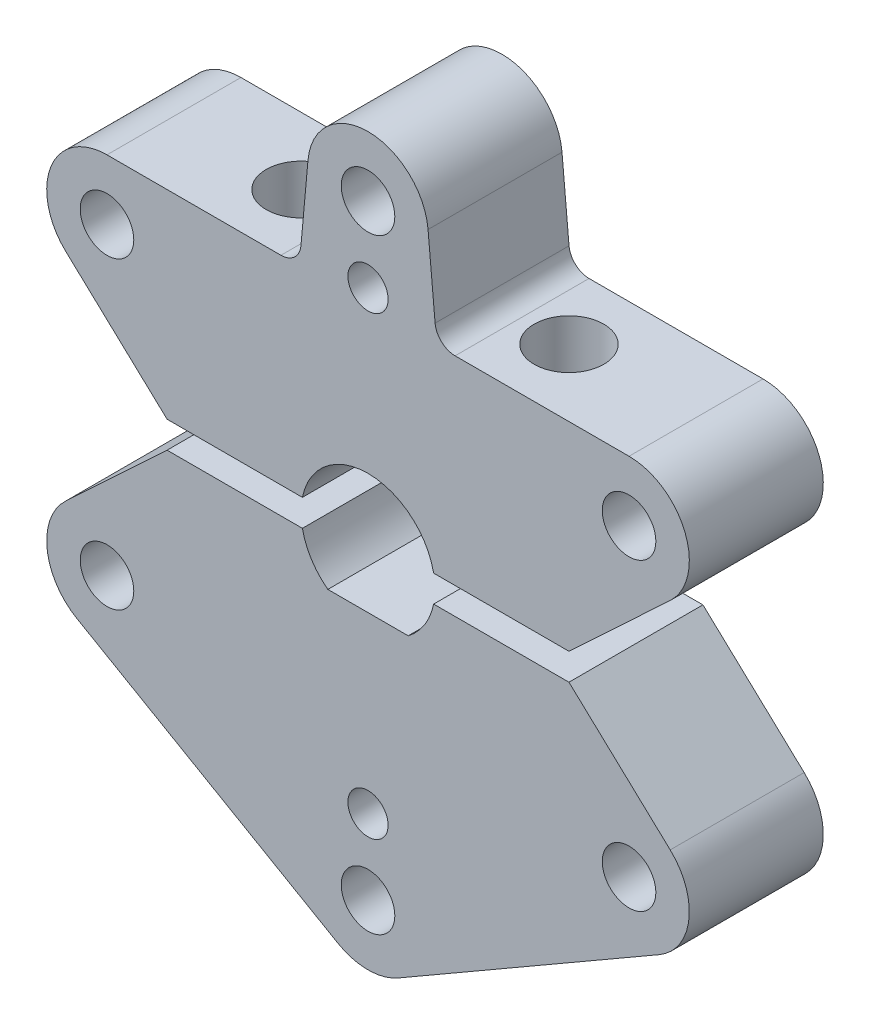
SolidWorks part; units mm, degrees
material "6061 合金"
ref_plane "前视基准面" through (0, 0, 0) normal (0, 0, 1) x (1, 0, 0)
ref_plane "上视基准面" through (0, 0, 0) normal (0, 1, 0) x (1, 0, 0)
ref_plane "右视基准面" through (0, 0, 0) normal (1, 0, 0) x (0, 0, -1)
sketch "草图1" plane through (0, 0, 0) normal (0, 0, 1) x (1, 0, 0)
  line L0 (0, 22.5) -> (0, 22.6) construction
  line L1 (0, 22.5) -> (-19.4856, 11.25) construction
  line L2 (-19.4856, 11.25) -> (-19.4856, -11.25) construction
  line L3 (-19.4856, -11.25) -> (0, -22.5) construction
  line L4 (0, -22.5) -> (19.4856, -11.25) construction
  line L5 (19.4856, -11.25) -> (19.4856, 11.25) construction
  line L6 (19.4856, 11.25) -> (0, 22.5) construction
  line L7 (-19.4856, 11.25) -> (-19.4856, 11.35) construction
  line L8 (19.4856, 11.25) -> (19.4856, 11.35) construction
  line L9 (-19.4856, -11.25) -> (-19.4856, -11.35) construction
  line L10 (0, -22.5) -> (0, -22.6) construction
  line L11 (19.4856, -11.25) -> (19.4856, -11.35) construction
  line L12 (-3, -4) -> (3, -4)
  line L13 (-15, 1) -> (-22.5579, 8.062)
  line L14 (-19.4856, 15.85) -> (-6.5, 15.85)
  line L15 (-5.0061, 17.2147) -> (-4.4817, 23.0059)
  line L16 (4.4817, 23.0059) -> (5.0061, 17.2147)
  line L17 (6.5, 15.85) -> (19.4856, 15.85)
  line L18 (22.5579, 8.062) -> (15, 1)
  line L19 (15, 1) -> (4.899, 1)
  line L20 (-5.1297, 15.85) -> (5.1297, 15.85) construction
  line L21 (-15, -1) -> (-22.5579, -8.062)
  line L22 (-4.899, 1) -> (-15, 1)
  line L23 (-21.7356, -15.2471) -> (-2.25, -26.4971)
  line L24 (2.25, -26.4971) -> (21.7356, -15.2471)
  line L25 (22.5579, -8.062) -> (15, -1)
  line L26 (15, -1) -> (4.899, -1)
  line L27 (-4.899, -1) -> (-15, -1)
  circle A0 centre (0, 0) radius 22.5 construction
  circle A1 centre (-19.4856, 11.35) radius 2
  circle A2 centre (0, 22.6) radius 2
  circle A3 centre (19.4856, 11.35) radius 2
  circle A4 centre (-19.4856, -11.35) radius 2
  circle A5 centre (0, -22.6) radius 2
  circle A6 centre (19.4856, -11.35) radius 2
  arc A7 (3, -4) -> (4.899, -1) centre (0, 0) ccw
  arc A8 (19.4856, 15.85) -> (22.5579, 8.062) centre (19.4856, 11.35) cw
  arc A9 (-22.5579, 8.062) -> (-19.4856, 15.85) centre (-19.4856, 11.35) cw
  arc A10 (-4.4817, 23.0059) -> (4.4817, 23.0059) centre (0, 22.6) cw
  arc A11 (5.0061, 17.2147) -> (6.5, 15.85) centre (6.5, 17.35) ccw
  arc A12 (-6.5, 15.85) -> (-5.0061, 17.2147) centre (-6.5, 17.35) ccw
  arc A13 (21.7356, -15.2471) -> (22.5579, -8.062) centre (19.4856, -11.35) ccw
  arc A14 (-2.25, -26.4971) -> (2.25, -26.4971) centre (0, -22.6) ccw
  arc A15 (-22.5579, -8.062) -> (-21.7356, -15.2471) centre (-19.4856, -11.35) ccw
  arc A16 (-4.899, -1) -> (-3, -4) centre (0, 0) ccw
  arc A17 (4.899, 1) -> (-4.899, 1) centre (0, 0) ccw
  dimension "D1" = 45
  dimension "D2" = 4
  dimension "D4" = 5
  dimension "D6" = 4.5
  dimension "D10" = 1.5
  dimension "D11" = 4.5
  dimension "D3" = 0.1
  dimension "D5" = 4
  dimension "D7" = 13
  dimension "D8" = 30
  dimension "D9" = 1
  dimension "D12" = 1
extrude "凸台-拉伸1" add sketch "草图1" along normal blind 10
cosmetic thread "装饰螺纹线3" parameters "D2"=5
cosmetic thread "装饰螺纹线4" parameters "D2"=5
cosmetic thread "装饰螺纹线5" parameters "D2"=5
cosmetic thread "装饰螺纹线6" parameters "D2"=5
cosmetic thread "装饰螺纹线7" parameters "D2"=5
cosmetic thread "装饰螺纹线8" parameters "D2"=5
sketch "草图2" plane through (0, 15.85, 0) normal (0, 1, 0) x (1, 0, 0)
  line L0 (-10, -5) -> (10, -5) construction
  line L2 (0, 0) -> (0, -5) construction
  line L3 (0, -5) -> (0, -10) construction
  line L4 (-4.4817, -10) -> (4.4817, -10) construction
  circle A0 centre (-10, -5) radius 2.6
  circle A1 centre (10, -5) radius 2.6
  dimension "D2" = 5.2
  dimension "D1" = 20
extrude "切除-拉伸1" cut sketch "草图2" against normal up to surface (14.85 mm away) up to face at (-9.9495, 1, 5)
sketch "草图3" plane through (0, 15.85, 0) normal (0, 1, 0) x (1, 0, 0)
  circle A0 centre (-10, -5) radius 2
  circle A1 centre (10, -5) radius 2
  dimension "D1" = 4
extrude "切除-拉伸2" cut sketch "草图3" against normal through all
cosmetic thread "装饰螺纹线1" parameters "D2"=5
cosmetic thread "装饰螺纹线2" parameters "D2"=5
sketch "草图4" plane through (0, 0, 10) normal (0, 0, 1) x (1, 0, 0)
  circle A0 centre (0, 0) radius 17 construction
  circle A1 centre (0, -17) radius 1.5
  circle A2 centre (0, 17) radius 1.5
  point P9 (0, 0)
  dimension "D1" = 2
  dimension "D2" = 34
  dimension "D3" = 3
extrude "切除-拉伸3" cut sketch "草图4" against normal through all
